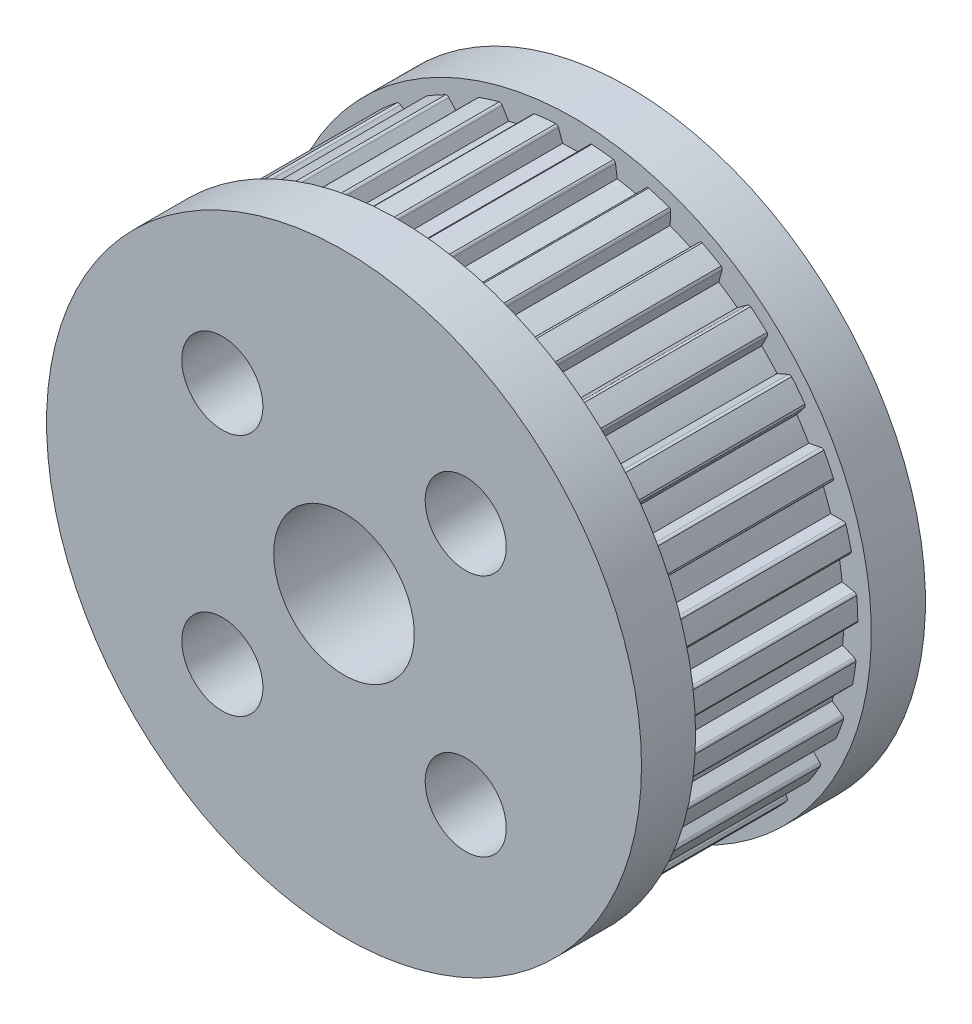
SolidWorks part; units mm, degrees
ref_plane "Plan de face" through (0, 0, 0) normal (0, 0, 1) x (1, 0, 0)
ref_plane "Plan de dessus" through (0, 0, 0) normal (0, 1, 0) x (1, 0, 0)
ref_plane "Plan de droite" through (0, 0, 0) normal (1, 0, 0) x (0, 0, -1)
sketch "Esquisse1" plane through (0, 0, 0) normal (0, 0, 1) x (1, 0, 0)
  line L0 (0, 0) -> (0, 11.7813) construction
  circle A0 centre (0, 0) radius 10.5
  dimension "D1" = 21
extrude "Boss.-Extru.1" add sketch "Esquisse1" along normal blind 6.5 contours A0
sketch "Esquisse2" plane through (0, 0, 6.5) normal (0, 0, 1) x (1, 0, 0)
  line L9 (0, 0) -> (0, 11.354) construction
  line L11 (-0.415, 9.9718) -> (-0.5707, 10.3994)
  line L12 (-0.6919, 10.4805) -> (-1.016, 10.4641)
  line L14 (0.415, 9.9718) -> (0.5707, 10.3994)
  line L15 (0.6919, 10.4805) -> (1.0144, 10.4641)
  line L16 (-1.016, 10.4641) -> (-1.016, 11.1126)
  line L17 (-1.016, 11.1126) -> (1.0144, 11.1126)
  line L18 (1.0144, 11.1126) -> (1.0144, 10.4641)
  line L22 (-0.415, 9.9718) -> (0.415, 9.9718) construction
  line L23 (-0.601, 10.4828) -> (-0.7038, 10.3321) construction
  circle A0 centre (0, 0) radius 10
  circle A1 centre (0, 0) radius 10.5 construction
  arc A2 (-0.415, 9.9718) -> (0.415, 9.9718) centre (0, 0) cw
  arc A5 (-0.5707, 10.3994) -> (-0.6919, 10.4805) centre (-0.6821, 10.364) ccw
  arc A6 (0.5707, 10.3994) -> (0.6919, 10.4805) centre (0.6821, 10.364) cw
  point P11 (0, 9.9718)
  dimension "D1" = 20
  dimension "D8" = 52.785
  dimension "D2" = 70
  dimension "D3" = 0.186
  dimension "D5" = 0.83
  dimension "D7" = 0.415
extrude "Enlèv. mat.-Extru.1" cut sketch "Esquisse2" against normal up to next contours L17 L18 L15 A6 L14 A2 L11 A5 L12 L16
pattern_circular "Répétition circulaire1" count 31 every 11.612 about axis through (0, 0, 0) along (0, 0, 1) of "Enlèv. mat.-Extru.1"
sketch "Esquisse3" plane through (0, 0, 6.5) normal (0, 0, 1) x (1, 0, 0)
  circle A0 centre (0, 0) radius 11
  dimension "D1" = 22
extrude "Boss.-Extru.2" add sketch "Esquisse3" along normal blind 2
sketch "Esquisse4" plane through (0, 0, 0) normal (0, 0, -1) x (-1, 0, 0)
  circle A0 centre (0, 0) radius 11
extrude "Boss.-Extru.3" add sketch "Esquisse4" along normal blind 2
sketch "Esquisse5" plane through (0, 0, -2) normal (0, 0, -1) x (-1, 0, 0)
  line L1 (-4.5, -4.5) -> (4.5, -4.5) construction
  line L2 (-4.5, -4.5) -> (-4.5, 4.5) construction
  line L3 (-4.5, 4.5) -> (4.5, 4.5) construction
  line L4 (4.5, -4.5) -> (4.5, 4.5) construction
  line L5 (-4.5, -4.5) -> (4.5, 4.5) construction
  line L6 (-4.5, 4.5) -> (4.5, -4.5) construction
  circle A0 centre (0, 0) radius 2.6
  circle A1 centre (-4.5, 4.5) radius 1.5
  circle A2 centre (-4.5, -4.5) radius 1.5
  circle A3 centre (4.5, -4.5) radius 1.5
  circle A4 centre (4.5, 4.5) radius 1.5
  dimension "D1" = 5.2
  dimension "D3" = 3
  dimension "D4" = 3
  dimension "D5" = 3
  dimension "D6" = 3
  dimension "D2" = 9
extrude "Enlèv. mat.-Extru.2" cut sketch "Esquisse5" against normal through all
sketch "Esquisse6" plane through (0, 0, -2) normal (0, 0, -1) x (-1, 0, 0)
  circle A0 centre (0, 0) radius 9.65
  dimension "D1" = 19.3
extrude "Enlèv. mat.-Extru.3" cut sketch "Esquisse6" against normal blind 5
